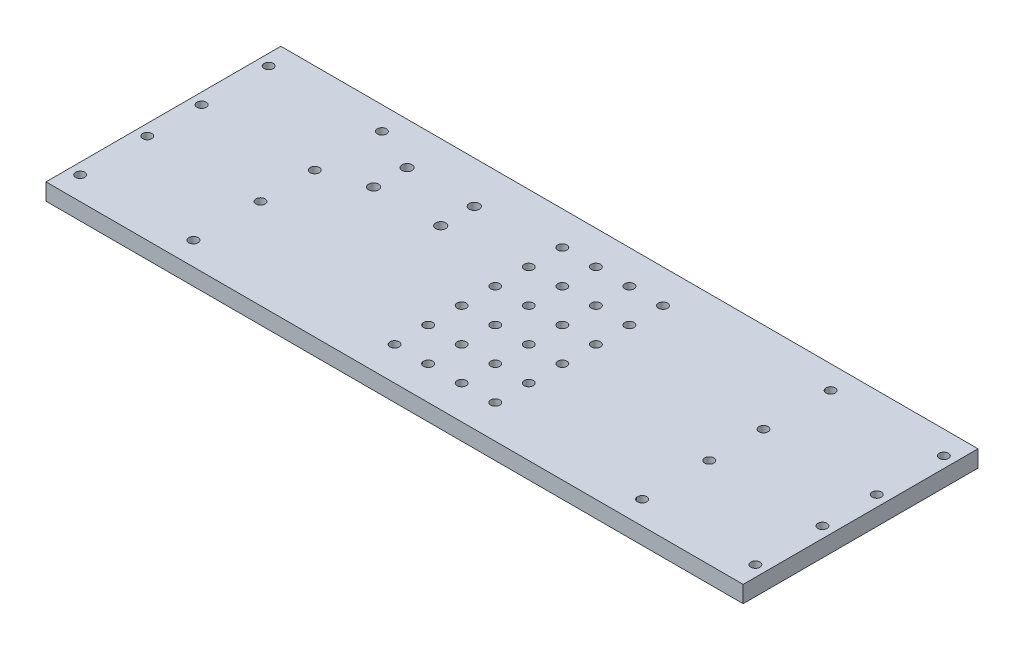
SolidWorks part; units mm, degrees
ref_plane "Front Plane" through (0, 0, 0) normal (0, 0, 1) x (1, 0, 0)
ref_plane "Top Plane" through (0, 0, 0) normal (0, 1, 0) x (1, 0, 0)
ref_plane "Right Plane" through (0, 0, 0) normal (1, 0, 0) x (0, 0, -1)
sketch "Sketch1" plane through (0, 0, 0) normal (0, 1, 0) x (1, 0, 0)
  line L1 (-80.1632, 25.6013) -> (183.7428, 25.6013)
  line L2 (-80.1632, 25.6013) -> (-80.1632, -63.2987)
  line L3 (-80.1632, -63.2987) -> (183.7428, -63.2987)
  line L4 (183.7428, 25.6013) -> (183.7428, -63.2987)
  dimension "D1" = 263.906
  dimension "D2" = 88.9
extrude "Boss-Extrude1" add sketch "Sketch1" along normal blind 6.35
hole_wizard "#8-32 Tapped Hole2" positions "Sketch3" profile "Sketch2" tap size "#8-32" standard "ANSI Inch" end condition through all
sketch "Sketch3" plane through (0, 6.35, 0) normal (0, 1, 0) x (1, 0, 0)
  line L0 (-54.5727, 36.1563) -> (-54.5727, -27.7254) construction
  line L3 (-90.8683, 4.1256) -> (-38.4961, 4.1256) construction
  line L6 (-80.1632, -18.8487) -> (-22.0432, -18.8487) construction
  line L7 (-80.1632, 25.6013) -> (-80.1632, -63.2987) construction
  line L10 (51.7898, 25.6013) -> (51.7898, -72.9648) construction
  line L11 (183.7428, 25.6013) -> (-80.1632, 25.6013) construction
  point P0 (-76.0039, 16.8256)
  point P31 (-33.1414, 16.8256)
  point P32 (-33.1414, -8.5744)
  point P33 (-76.0039, -8.5744)
  point P34 (-76.0039, -29.123)
  point P35 (-33.1414, -29.123)
  point P36 (-33.1414, -54.523)
  point P37 (-76.0039, -54.523)
  point P38 (179.5836, 16.8256)
  point P39 (179.5836, -8.5744)
  point P40 (179.5836, -29.123)
  point P41 (179.5836, -54.523)
  point P42 (136.7211, -54.523)
  point P43 (136.7211, -29.123)
  point P44 (136.7211, -8.5744)
  point P45 (136.7211, 16.8256)
  dimension "D1" = 42.8625
  dimension "D2" = 25.4
  dimension "D3" = 25.5905
  dimension "D4" = 21.4757
sketch "Sketch2" plane through (-76.0039, 6.35, -16.8256) normal (1, 0, 0) x (0, 0, 1)
  line L0 (0, 0) -> (0, 6.35)
  line L1 (0, 6.35) -> (1.7272, 6.35)
  line L2 (1.7272, 6.35) -> (1.7272, 0)
  line L5 (1.7272, 0) -> (0, 0)
  line L11 (0, -6.35) -> (0, 107.95) construction
  dimension "Thread Major Dia." = 3.4544
  dimension "Thru Tap Drill Depth" = 6.35
hole_wizard "#10-24 Tapped Hole1" positions "Sketch5" profile "Sketch4" tap size "#10-24" standard "ANSI Inch" end condition through all
sketch "Sketch5" plane through (0, 6.35, 0) normal (0, 1, 0) x (1, 0, 0)
  line L0 (-3.7727, 25.6013) -> (-3.7727, -63.2987) construction
  line L1 (183.7428, 25.6013) -> (-80.1632, 25.6013) construction
  line L2 (-80.1632, -63.2987) -> (183.7428, -63.2987) construction
  line L5 (-80.1632, 25.6013) -> (-80.1632, -63.2987) construction
  point P0 (-16.4727, 9.7263)
  point P15 (-16.4727, -2.9737)
  point P20 (8.9273, -2.9737)
  point P21 (8.9273, 9.7263)
  dimension "D1" = 76.3905
  dimension "D2" = 25.4
  dimension "D3" = 15.875
  dimension "D4" = 12.7
sketch "Sketch4" plane through (-16.4727, 6.35, -9.7263) normal (1, 0, 0) x (0, 0, 1)
  line L0 (0, 0) -> (0, 6.35)
  line L1 (0, 6.35) -> (1.8986, 6.35)
  line L2 (1.8986, 6.35) -> (1.8986, 0)
  line L5 (1.8986, 0) -> (0, 0)
  line L11 (0, -6.35) -> (0, 107.95) construction
  dimension "Thread Major Dia." = 3.7973
  dimension "Thru Tap Drill Depth" = 6.35
hole_wizard "#8-32 Tapped Hole3" positions "Sketch7" profile "Sketch6" tap size "#8-32" standard "ANSI Inch" end condition through all
sketch "Sketch7" plane through (0, 6.35, 0) normal (0, 1, 0) x (1, 0, 0)
  line L0 (51.7898, 25.6013) -> (51.7898, -78.6777) construction
  line L1 (183.7428, 25.6013) -> (-80.1632, 25.6013) construction
  line L2 (-80.1632, 25.6013) -> (-80.1632, -63.2987) construction
  line L3 (-80.1632, -63.2987) -> (183.7428, -63.2987) construction
  line L4 (64.4898, -50.5987) -> (77.1898, -50.5987) construction
  line L5 (64.4898, -50.5987) -> (64.4898, -37.8987) construction
  point P0 (39.0898, -50.5987)
  point P16 (64.4898, -50.5987)
  point P28 (51.7898, -50.5987)
  point P29 (77.1898, -50.5987)
  point P30 (51.7898, -37.8987)
  point P31 (77.1898, -37.8987)
  point P32 (51.7898, -25.1987)
  point P33 (77.1898, -25.1987)
  point P34 (51.7898, -12.4987)
  point P35 (77.1898, -12.4987)
  point P36 (51.7898, 0.2013)
  point P37 (77.1898, 0.2013)
  point P38 (51.7898, 12.9013)
  point P39 (77.1898, 12.9013)
  point P40 (39.0898, -37.8987)
  point P41 (64.4898, -37.8987)
  point P42 (39.0898, -25.1987)
  point P43 (64.4898, -25.1987)
  point P44 (39.0898, -12.4987)
  point P45 (64.4898, -12.4987)
  point P46 (39.0898, 0.2013)
  point P47 (64.4898, 0.2013)
  point P48 (39.0898, 12.9013)
  point P49 (64.4898, 12.9013)
  dimension "D1" = 131.953
  dimension "D2" = 25.4
  dimension "D3" = 12.7
  dimension "D6" = 12.7
  dimension "D7" = 12.7
  dimension "D4" = 2
  dimension "D5" = 6
sketch "Sketch6" plane through (39.0898, 6.35, 50.5987) normal (1, 0, 0) x (0, 0, 1)
  line L0 (0, 0) -> (0, 6.35)
  line L1 (0, 6.35) -> (1.7272, 6.35)
  line L2 (1.7272, 6.35) -> (1.7272, 0)
  line L5 (1.7272, 0) -> (0, 0)
  line L11 (0, -6.35) -> (0, 107.95) construction
  dimension "Thread Major Dia." = 3.4544
  dimension "Thru Tap Drill Depth" = 6.35
